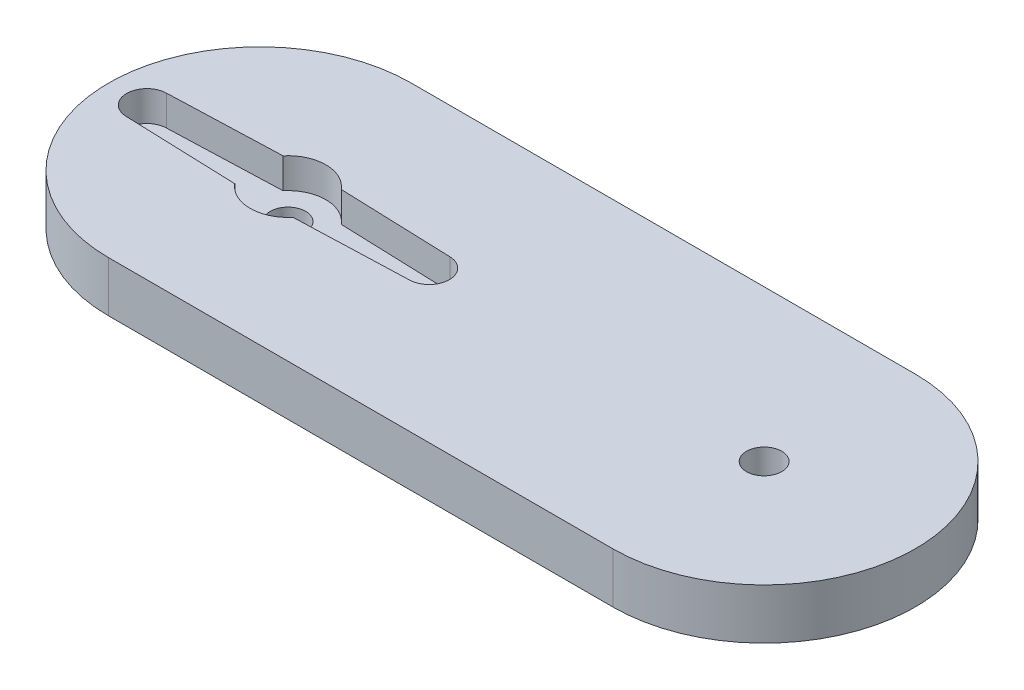
SolidWorks part; units mm, degrees
material "ABS"
ref_plane "Plano frontal" through (0, 0, 0) normal (0, 0, 1) x (1, 0, 0)
ref_plane "Plano superior" through (0, 0, 0) normal (0, 1, 0) x (1, 0, 0)
ref_plane "Plano direito" through (0, 0, 0) normal (1, 0, 0) x (0, 0, -1)
sketch "Esboço3" plane through (0, 0, 0) normal (0, 1, 0) x (1, 0, 0)
  line L2 (-50, 15) -> (0, 15)
  line L3 (-50, -15) -> (0, -15)
  arc A0 (0, 15) -> (0, -15) centre (0, 0) cw
  arc A1 (-50, 15) -> (-50, -15) centre (-50, 0) ccw
  point P4 (0, 0)
  dimension "D2" = 30
  dimension "D4" = 15
  dimension "D1" = 50
  dimension "D5" = 50
extrude "Ressalto-extrusão2" add sketch "Esboço3" along normal blind 5
sketch "Esboço4" plane through (0, 5, 0) normal (0, 1, 0) x (1, 0, 0)
  line L0 (-65, 0) -> (15, 0) construction
  arc A0 (-50, 15) -> (-50, -15) centre (-50, 0) ccw construction
  arc A1 (0, -15) -> (0, 15) centre (0, 0) ccw construction
  circle A3 centre (0, 0) radius 1.75
  dimension "D1" = 3.5
extrude "Corte-extrusão1" cut sketch "Esboço4" against normal blind 10
sketch "Esboço6" plane through (0, 5, 0) normal (0, 1, 0) x (1, 0, 0)
  line L0 (-46.9774, 2.4891) -> (-47.2106, 2.4974)
  line L1 (-61.2815, 1.9987) -> (-50.0961, 2.3951)
  line L2 (-61.2815, -1.9987) -> (-50.0961, -2.3951)
  line L3 (-33.1398, -1.9987) -> (-44.3252, -2.3951)
  line L4 (-33.1398, 1.9987) -> (-44.3252, 2.3951)
  line L5 (0, 15) -> (-50, 15) construction
  line L6 (-50, -15) -> (0, -15) construction
  line L7 (-47.4439, 2.4891) -> (-47.2106, 2.4974)
  line L8 (-47.4439, -2.4891) -> (-47.2106, -2.4974)
  line L9 (-46.9774, -2.4891) -> (-47.2106, -2.4974)
  arc A0 (-50.0961, -2.3951) -> (-44.3252, -2.3951) centre (-47.2106, 0) ccw
  circle A1 centre (-47.2106, 0) radius 2.5
  arc A2 (-61.1776, -1.9997) -> (-61.2815, 1.9987) centre (-61.2106, 0) cw
  arc A3 (-33.2436, -1.9997) -> (-33.1398, 1.9987) centre (-33.2106, 0) ccw
  arc A4 (-44.3252, 2.3951) -> (-50.0961, 2.3951) centre (-47.2106, 0) ccw
  arc A8 (-50, 15) -> (-50, -15) centre (-50, 0) ccw construction
  dimension "D1" = 28
  dimension "D3" = 47.2106
  dimension "D9" = 2
  dimension "D10" = 2
  dimension "D2" = 2.7894
  dimension "D5" = 4.7902
  dimension "D4" = 30
  dimension "D6" = 3.9998
  dimension "D7" = 3.9975
  dimension "D8" = 4.7902
extrude "Corte-extrusão2" cut sketch "Esboço6" against normal blind 3
sketch "Esboço7" plane through (0, 5, 0) normal (0, 1, 0) x (1, 0, 0)
  circle A0 centre (-47.2106, 0) radius 2.5
extrude "Corte-extrusão3" cut sketch "Esboço7" against normal blind 3
sketch "Esboço12" plane through (0, 2, 0) normal (0, 1, 0) x (1, 0, 0)
  circle A0 centre (-47.2106, 0) radius 1.75
extrude "Corte-extrusão5" cut sketch "Esboço12" against normal blind 10
